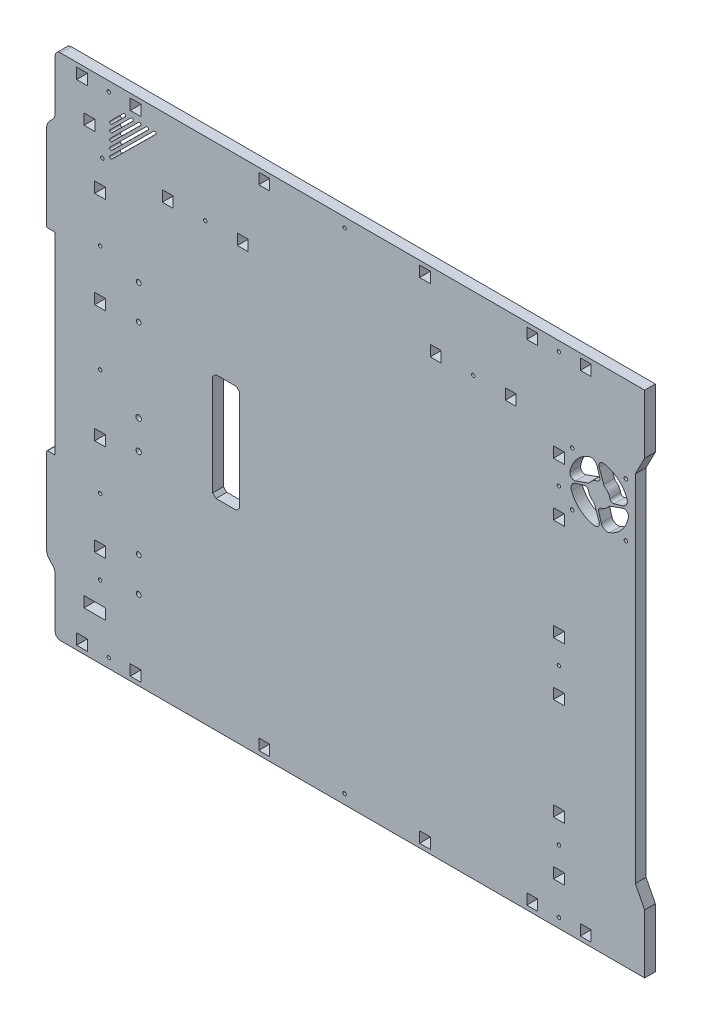
SolidWorks part; units mm, degrees
ref_plane "Front" through (0, 0, 0) normal (0, 0, 1) x (1, 0, 0)
ref_plane "Top" through (0, 0, 0) normal (0, 1, 0) x (1, 0, 0)
ref_plane "Right" through (0, 0, 0) normal (1, 0, 0) x (0, 0, -1)
sketch "Эскиз1" plane through (0, 0, 0) normal (0, 0, 1) x (1, 0, 0)
  line L0 (-464.1911, 417.3938) -> (-464.1911, 427.3938)
  line L1 (-464.1911, 427.3938) -> (-454.0911, 427.3938)
  line L2 (-454.0911, 427.3938) -> (-454.0911, 417.3938)
  line L3 (-454.0911, 417.3938) -> (-464.1911, 417.3938)
  line L4 (-464.1911, 367.3938) -> (-464.1911, 377.3938)
  line L5 (-464.1911, 377.3938) -> (-454.0911, 377.3938)
  line L6 (-454.0911, 377.3938) -> (-454.0911, 367.3938)
  line L7 (-454.0911, 367.3938) -> (-464.1911, 367.3938)
  line L8 (-464.1911, 137.3938) -> (-454.0911, 137.3938)
  line L9 (-454.0911, 137.3938) -> (-454.0911, 127.3938)
  line L10 (-454.0911, 127.3938) -> (-464.1911, 127.3938)
  line L11 (-464.1911, 127.3938) -> (-464.1911, 137.3938)
  line L12 (-464.1911, 87.3938) -> (-454.0911, 87.3938)
  line L13 (-454.0911, 87.3938) -> (-454.0911, 77.3938)
  line L14 (-454.0911, 77.3938) -> (-464.1911, 77.3938)
  line L15 (-464.1911, 77.3938) -> (-464.1911, 87.3938)
  line L16 (-729.0934, 510.9938) -> (-729.0934, 500.8938)
  line L17 (-729.0934, 500.8938) -> (-739.0934, 500.8938)
  line L18 (-739.0934, 500.8938) -> (-739.0934, 510.9938)
  line L19 (-739.0934, 510.9938) -> (-729.0934, 510.9938)
  line L20 (-729.0934, 43.7938) -> (-739.0934, 43.7938)
  line L21 (-739.0934, 43.7938) -> (-739.0934, 53.8938)
  line L22 (-739.0934, 53.8938) -> (-729.0934, 53.8938)
  line L23 (-729.0934, 53.8938) -> (-729.0934, 43.7938)
  line L24 (-429.0934, 43.7938) -> (-439.0934, 43.7938)
  line L25 (-439.0934, 43.7938) -> (-439.0934, 53.8938)
  line L26 (-439.0934, 53.8938) -> (-429.0934, 53.8938)
  line L27 (-429.0934, 53.8938) -> (-429.0934, 43.7938)
  line L28 (-429.0934, 510.9938) -> (-429.0934, 500.8938)
  line L29 (-429.0934, 500.8938) -> (-439.0934, 500.8938)
  line L30 (-439.0934, 500.8938) -> (-439.0934, 510.9938)
  line L31 (-439.0934, 510.9938) -> (-429.0934, 510.9938)
  line L32 (-579.0934, 510.9938) -> (-579.0934, 500.8938)
  line L33 (-579.0934, 500.8938) -> (-589.0934, 500.8938)
  line L34 (-589.0934, 500.8938) -> (-589.0934, 510.9938)
  line L35 (-589.0934, 510.9938) -> (-579.0934, 510.9938)
  line L36 (-579.0934, 43.7938) -> (-589.0934, 43.7938)
  line L37 (-589.0934, 43.7938) -> (-589.0934, 53.8938)
  line L38 (-589.0934, 53.8938) -> (-579.0934, 53.8938)
  line L39 (-579.0934, 53.8938) -> (-579.0934, 43.7938)
  line L40 (-899.0934, 510.9938) -> (-899.0934, 500.8938)
  line L41 (-899.0934, 500.8938) -> (-909.0934, 500.8938)
  line L42 (-909.0934, 500.8938) -> (-909.0934, 510.9938)
  line L43 (-909.0934, 510.9938) -> (-899.0934, 510.9938)
  line L44 (-899.0934, 43.7938) -> (-909.0934, 43.7938)
  line L45 (-909.0934, 43.7938) -> (-909.0934, 53.8938)
  line L46 (-909.0934, 53.8938) -> (-899.0934, 53.8938)
  line L47 (-899.0934, 53.8938) -> (-899.0934, 43.7938)
  line L48 (-849.0934, 510.9938) -> (-849.0934, 500.8938)
  line L49 (-849.0934, 500.8938) -> (-859.0934, 500.8938)
  line L50 (-859.0934, 500.8938) -> (-859.0934, 510.9938)
  line L51 (-859.0934, 510.9938) -> (-849.0934, 510.9938)
  line L52 (-849.0934, 43.7938) -> (-859.0934, 43.7938)
  line L53 (-859.0934, 43.7938) -> (-859.0934, 53.8938)
  line L54 (-859.0934, 53.8938) -> (-849.0934, 53.8938)
  line L55 (-849.0934, 53.8938) -> (-849.0934, 43.7938)
  line L56 (-479.0934, 510.9938) -> (-479.0934, 500.8938)
  line L57 (-479.0934, 500.8938) -> (-489.0934, 500.8938)
  line L58 (-489.0934, 500.8938) -> (-489.0934, 510.9938)
  line L59 (-489.0934, 510.9938) -> (-479.0934, 510.9938)
  line L60 (-479.0934, 43.7938) -> (-489.0934, 43.7938)
  line L61 (-489.0934, 43.7938) -> (-489.0934, 53.8938)
  line L62 (-489.0934, 53.8938) -> (-479.0934, 53.8938)
  line L63 (-479.0934, 53.8938) -> (-479.0934, 43.7938)
  line L64 (-882.0934, 417.3938) -> (-892.1934, 417.3938)
  line L65 (-892.1934, 417.3938) -> (-892.1934, 427.3938)
  line L66 (-892.1934, 427.3938) -> (-882.0934, 427.3938)
  line L67 (-882.0934, 427.3938) -> (-882.0934, 417.3938)
  line L68 (-882.0934, 87.3938) -> (-882.0934, 77.3938)
  line L69 (-882.0934, 77.3938) -> (-902.1934, 77.3938)
  line L70 (-902.1934, 77.3938) -> (-902.1934, 87.3938)
  line L71 (-902.1934, 87.3938) -> (-882.0934, 87.3938)
  line L72 (-882.0934, 327.3938) -> (-892.1934, 327.3938)
  line L73 (-892.1934, 327.3938) -> (-892.1934, 337.3938)
  line L74 (-892.1934, 337.3938) -> (-882.0934, 337.3938)
  line L75 (-882.0934, 337.3938) -> (-882.0934, 327.3938)
  line L76 (-892.0934, 467.3938) -> (-902.1934, 467.3938)
  line L77 (-902.1934, 467.3938) -> (-902.1934, 477.3938)
  line L78 (-902.1934, 477.3938) -> (-892.0934, 477.3938)
  line L79 (-892.0934, 477.3938) -> (-892.0934, 467.3938)
  line L80 (-882.0934, 137.3938) -> (-882.0934, 127.3938)
  line L81 (-882.0934, 127.3938) -> (-892.1934, 127.3938)
  line L82 (-892.1934, 127.3938) -> (-892.1934, 137.3938)
  line L83 (-892.1934, 137.3938) -> (-882.0934, 137.3938)
  line L84 (-882.0934, 227.3938) -> (-882.0934, 217.3938)
  line L85 (-882.0934, 217.3938) -> (-892.1934, 217.3938)
  line L86 (-892.1934, 217.3938) -> (-892.1934, 227.3938)
  line L87 (-892.1934, 227.3938) -> (-882.0934, 227.3938)
  line L88 (-929.0934, 509.8938) -> (-929.0934, 464.0359)
  line L89 (-932.0224, 456.9648) -> (-934.1645, 454.8227)
  line L90 (-937.0934, 447.7516) -> (-937.0934, 368.3938)
  line L91 (-936.0934, 367.3938) -> (-929.0934, 367.3938)
  line L92 (-929.0934, 367.3938) -> (-929.0934, 187.3938)
  line L93 (-929.0934, 187.3938) -> (-936.0934, 187.3938)
  line L94 (-937.0934, 186.3938) -> (-937.0934, 107.0359)
  line L95 (-934.1645, 99.9648) -> (-932.0224, 97.8227)
  line L96 (-929.0934, 90.7516) -> (-929.0934, 44.8938)
  line L97 (-924.0934, 39.8938) -> (-379.0934, 39.8938)
  line L98 (-379.0934, 39.8938) -> (-379.0934, 94.8938)
  line L99 (-379.0934, 94.8938) -> (-387.8237, 111.8938)
  line L100 (-387.8237, 442.8938) -> (-387.8237, 111.8938)
  line L101 (-387.8237, 442.8938) -> (-379.0934, 459.8938)
  line L102 (-379.0934, 459.8938) -> (-379.0934, 514.8938)
  line L103 (-379.0934, 514.8938) -> (-924.0934, 514.8938)
  line L104 (-858.3282, 495.2829) -> (-877.8807, 475.9452)
  line L105 (-876.1228, 474.1677) -> (-856.5702, 493.5054)
  line L106 (-851.2572, 495.2438) -> (-877.9198, 468.8742)
  line L107 (-876.1618, 467.0967) -> (-849.4992, 493.4663)
  line L108 (-844.1863, 495.2047) -> (-877.9589, 461.8033)
  line L109 (-876.2009, 460.0257) -> (-842.4283, 493.4272)
  line L110 (-865.3991, 495.3219) -> (-877.8417, 483.0161)
  line L111 (-876.0837, 481.2386) -> (-863.6412, 493.5444)
  line L112 (-837.1153, 495.1657) -> (-877.9979, 454.7323)
  line L113 (-876.24, 452.9548) -> (-835.3573, 493.3882)
  line L114 (-399.5399, 409.2218) -> (-411.1831, 405.0651)
  line L115 (-422.0247, 395.5057) -> (-419.6678, 387.3479)
  line L116 (-443.532, 409.3405) -> (-431.8889, 413.4972)
  line L117 (-421.0473, 423.0567) -> (-423.4041, 431.2145)
  line L118 (-421.4766, 431.2772) -> (-417.3199, 419.6341)
  line L119 (-407.7605, 408.7925) -> (-399.6027, 411.1493)
  line L120 (-421.5798, 387.2963) -> (-425.7365, 398.9395)
  line L121 (-435.296, 409.7811) -> (-443.4538, 407.4242)
  line L122 (-819.0934, 451.8938) -> (-819.0934, 441.7938)
  line L123 (-819.0934, 441.7938) -> (-829.0934, 441.7938)
  line L124 (-829.0934, 441.7938) -> (-829.0934, 451.8938)
  line L125 (-829.0934, 451.8938) -> (-819.0934, 451.8938)
  line L126 (-499.0934, 451.8938) -> (-499.0934, 441.7938)
  line L127 (-499.0934, 441.7938) -> (-509.0934, 441.7938)
  line L128 (-509.0934, 441.7938) -> (-509.0934, 451.8938)
  line L129 (-509.0934, 451.8938) -> (-499.0934, 451.8938)
  line L130 (-749.0934, 451.8938) -> (-749.0934, 441.7938)
  line L131 (-749.0934, 441.7938) -> (-759.0934, 441.7938)
  line L132 (-759.0934, 441.7938) -> (-759.0934, 451.8938)
  line L133 (-759.0934, 451.8938) -> (-749.0934, 451.8938)
  line L134 (-569.0934, 451.8938) -> (-569.0934, 441.7938)
  line L135 (-569.0934, 441.7938) -> (-579.0934, 441.7938)
  line L136 (-579.0934, 441.7938) -> (-579.0934, 451.8938)
  line L137 (-579.0934, 451.8938) -> (-569.0934, 451.8938)
  line L138 (-464.1911, 272.3938) -> (-464.1911, 282.3938)
  line L139 (-464.1911, 282.3938) -> (-454.0911, 282.3938)
  line L140 (-454.0911, 282.3938) -> (-454.0911, 272.3938)
  line L141 (-454.0911, 272.3938) -> (-464.1911, 272.3938)
  line L142 (-464.1911, 222.3938) -> (-464.1911, 232.3938)
  line L143 (-464.1911, 232.3938) -> (-454.0911, 232.3938)
  line L144 (-454.0911, 232.3938) -> (-454.0911, 222.3938)
  line L145 (-454.0911, 222.3938) -> (-464.1911, 222.3938)
  line L146 (-782.0934, 324.3938) -> (-782.0934, 230.3938)
  line L147 (-779.0934, 227.3938) -> (-760.0934, 227.3938)
  line L148 (-757.0934, 230.3938) -> (-757.0934, 324.3938)
  line L149 (-760.0934, 327.3938) -> (-779.0934, 327.3938)
  line L150 (-782.0934, 324.3938) -> (-779.0934, 327.3938)
  line L151 (-760.0934, 327.3938) -> (-757.0934, 324.3938)
  line L152 (-757.0934, 230.3938) -> (-760.0934, 227.3938)
  line L153 (-782.0934, 230.3938) -> (-779.0934, 227.3938)
  circle A0 centre (-887.1434, 377.3938) radius 1.6
  circle A1 centre (-459.0934, 48.8438) radius 1.6
  circle A2 centre (-659.0934, 48.8438) radius 1.6
  circle A3 centre (-887.1434, 177.3938) radius 1.6
  circle A4 centre (-885.1434, 449.3938) radius 1.6
  circle A5 centre (-879.0934, 505.9438) radius 1.6
  circle A6 centre (-659.0934, 505.9438) radius 1.6
  circle A7 centre (-459.0934, 505.9438) radius 1.6
  circle A8 centre (-879.0934, 48.8438) radius 1.6
  circle A9 centre (-887.1434, 107.3938) radius 1.6
  circle A10 centre (-459.1411, 107.3938) radius 1.6
  circle A11 centre (-459.1411, 397.3938) radius 1.6
  arc A12 (-924.0934, 514.8938) -> (-929.0934, 509.8938) centre (-924.0934, 509.8938) ccw
  arc A13 (-932.0224, 456.9648) -> (-929.0934, 464.0359) centre (-939.0934, 464.0359) ccw
  arc A14 (-934.1645, 454.8227) -> (-937.0934, 447.7516) centre (-927.0934, 447.7516) ccw
  arc A15 (-937.0934, 368.3938) -> (-936.0934, 367.3938) centre (-936.0934, 368.3938) ccw
  arc A16 (-936.0934, 187.3938) -> (-937.0934, 186.3938) centre (-936.0934, 186.3938) ccw
  arc A17 (-937.0934, 107.0359) -> (-934.1645, 99.9648) centre (-927.0934, 107.0359) ccw
  arc A18 (-929.0934, 90.7516) -> (-932.0224, 97.8227) centre (-939.0934, 90.7516) ccw
  arc A19 (-929.0934, 44.8938) -> (-924.0934, 39.8938) centre (-924.0934, 44.8938) ccw
  arc A20 (-856.5702, 493.5054) -> (-858.3282, 495.2829) centre (-857.4492, 494.3941) ccw
  arc A21 (-877.8807, 475.9452) -> (-876.1228, 474.1677) centre (-877.0018, 475.0564) ccw
  arc A22 (-849.4992, 493.4663) -> (-851.2572, 495.2438) centre (-850.3782, 494.3551) ccw
  arc A23 (-877.9198, 468.8742) -> (-876.1618, 467.0967) centre (-877.0408, 467.9855) ccw
  arc A24 (-842.4283, 493.4272) -> (-844.1863, 495.2047) centre (-843.3073, 494.316) ccw
  arc A25 (-877.9589, 461.8033) -> (-876.2009, 460.0257) centre (-877.0799, 460.9145) ccw
  arc A26 (-863.6412, 493.5444) -> (-865.3991, 495.3219) centre (-864.5201, 494.4332) ccw
  arc A27 (-877.8417, 483.0161) -> (-876.0837, 481.2386) centre (-876.9627, 482.1274) ccw
  arc A28 (-835.3573, 493.3882) -> (-837.1153, 495.1657) centre (-836.2363, 494.2769) ccw
  arc A29 (-877.9979, 454.7323) -> (-876.24, 452.9548) centre (-877.119, 453.8435) ccw
  circle A30 centre (-887.1434, 277.3938) radius 1.6
  circle A31 centre (-446.6834, 434.4286) radius 1.6
  circle A32 centre (-446.6834, 384.4286) radius 1.6
  circle A33 centre (-396.6834, 384.4286) radius 1.6
  circle A34 centre (-396.6834, 434.4286) radius 1.6
  arc A35 (-411.7904, 383.3976) -> (-394.2473, 404.8099) centre (-421.5247, 409.2656) ccw
  arc A36 (-419.688, 399.2883) -> (-413.1421, 403.5527) centre (-421.536, 409.2812) ccw
  arc A37 (-431.2816, 435.1647) -> (-448.8246, 413.7525) centre (-421.5472, 409.2967) ccw
  arc A38 (-423.3839, 419.274) -> (-429.9298, 415.0096) centre (-421.536, 409.2812) ccw
  arc A39 (-395.6524, 419.0268) -> (-417.0647, 436.5698) centre (-421.5204, 409.2924) ccw
  arc A40 (-411.5431, 411.1291) -> (-415.8075, 417.675) centre (-421.536, 409.2812) ccw
  arc A41 (-447.404, 399.5468) -> (-425.9917, 382.0037) centre (-421.536, 409.2812) ccw
  arc A42 (-431.5133, 407.4445) -> (-427.2489, 400.8985) centre (-421.5204, 409.2924) ccw
  arc A43 (-419.6678, 387.3479) -> (-411.7904, 383.3976) centre (-413.9035, 389.0132) ccw
  arc A44 (-443.4538, 407.4242) -> (-447.404, 399.5468) centre (-441.7884, 401.66) ccw
  arc A45 (-399.6027, 411.1493) -> (-395.6524, 419.0268) centre (-401.268, 416.9136) ccw
  arc A46 (-423.4041, 431.2145) -> (-431.2816, 435.1647) centre (-429.1684, 429.5491) ccw
  arc A47 (-431.5133, 407.4445) -> (-435.296, 409.7811) centre (-434.4633, 406.8989) ccw
  arc A48 (-419.688, 399.2883) -> (-422.0247, 395.5057) centre (-419.1425, 396.3383) ccw
  arc A49 (-411.5431, 411.1291) -> (-407.7605, 408.7925) centre (-408.5931, 411.6746) ccw
  arc A50 (-423.3839, 419.274) -> (-421.0473, 423.0567) centre (-423.9294, 422.224) ccw
  arc A51 (-417.3199, 419.6341) -> (-415.8075, 417.675) centre (-413.5528, 420.979) ccw
  arc A52 (-431.8889, 413.4972) -> (-429.9298, 415.0096) centre (-433.2338, 417.2644) ccw
  arc A53 (-425.7365, 398.9395) -> (-427.2489, 400.8985) centre (-429.5037, 397.5946) ccw
  arc A54 (-411.1831, 405.0651) -> (-413.1421, 403.5527) centre (-409.8382, 401.298) ccw
  arc A55 (-448.8246, 413.7525) -> (-443.532, 409.3405) centre (-444.8769, 413.1076) ccw
  arc A56 (-417.0647, 436.5698) -> (-421.4766, 431.2772) centre (-417.7095, 432.6221) ccw
  arc A57 (-394.2473, 404.8099) -> (-399.5399, 409.2218) centre (-398.195, 405.4547) ccw
  arc A58 (-425.9917, 382.0037) -> (-421.5798, 387.2963) centre (-425.3469, 385.9514) ccw
  circle A59 centre (-789.0934, 446.8438) radius 1.6
  circle A60 centre (-539.0934, 446.8438) radius 1.6
  circle A61 centre (-459.1411, 252.3938) radius 1.6
  circle A62 centre (-851.1911, 113.8938) radius 2.25
  circle A63 centre (-851.1911, 365.8938) radius 2.25
  circle A64 centre (-851.1911, 333.8938) radius 2.25
  circle A65 centre (-851.1911, 145.8938) radius 2.25
  circle A66 centre (-851.1911, 256.3938) radius 2.5
  circle A67 centre (-851.1911, 229.3938) radius 2.5
extrude "Бобышка-Вытянуть1" add sketch "Эскиз1" along normal blind 10
